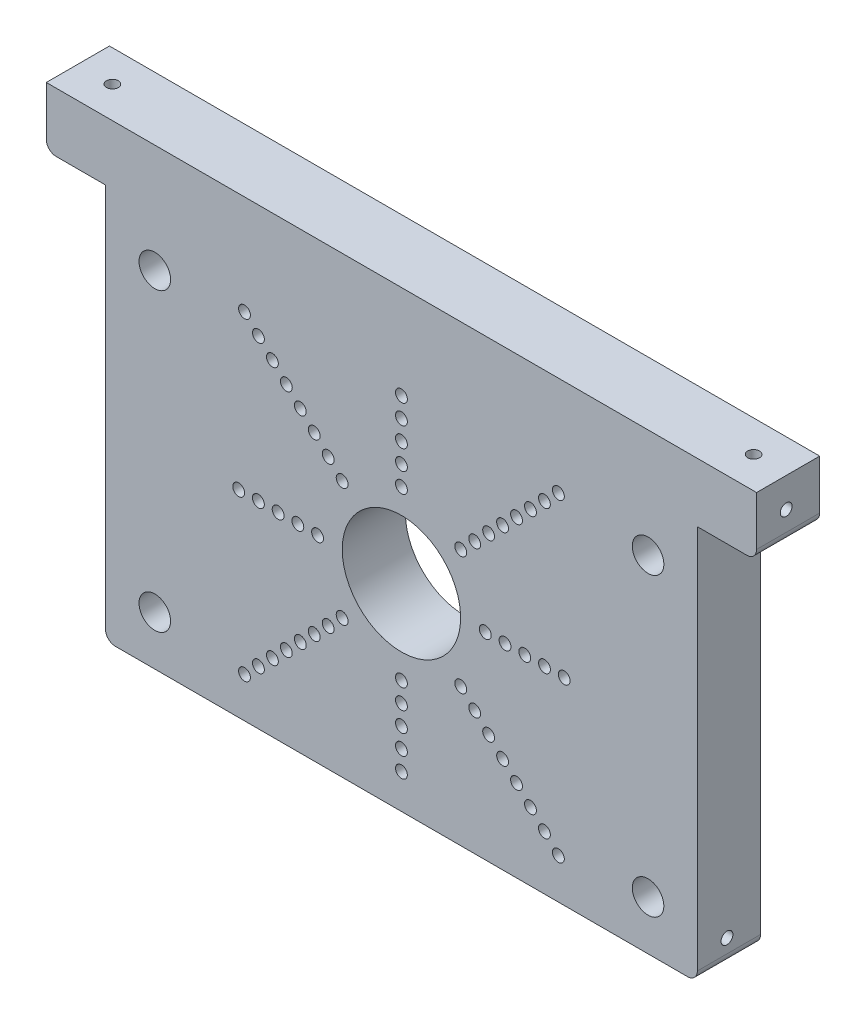
SolidWorks part; units mm, degrees
ref_plane "Front Plane" through (0, 0, 0) normal (0, 0, 1) x (1, 0, 0)
ref_plane "Top Plane" through (0, 0, 0) normal (0, 1, 0) x (1, 0, 0)
ref_plane "Right Plane" through (0, 0, 0) normal (1, 0, 0) x (0, 0, -1)
sketch "Sketch1" plane through (0, 0, 0) normal (0, 0, 1) x (1, 0, 0)
  line L1 (150, 100) -> (-150, 100)
  line L2 (150, 100) -> (150, -100)
  line L3 (150, -100) -> (-150, -100)
  line L4 (-150, 100) -> (-150, -100)
  circle A0 centre (125, 75) radius 8
  circle A1 centre (125, -75) radius 8
  circle A2 centre (-125, -75) radius 8
  circle A3 centre (-125, 75) radius 8
  point P0 (0, 0)
  dimension "D7" = 16
  dimension "D8" = 16
  dimension "D9" = 16
  dimension "D10" = 16
  dimension "D1" = 200
  dimension "D2" = 300
extrude "Boss-Extrude1" add sketch "Sketch1" along normal blind 32
sketch "Sketch2" plane through (0, 0, 32) normal (0, 0, 1) x (1, 0, 0)
  line L7 (-150, -100) -> (-150, 100) construction
  circle A2 centre (58.3363, -58.3363) radius 3
  circle A3 centre (51.2652, -51.2652) radius 3
  circle A4 centre (44.1942, -44.1942) radius 3
  circle A5 centre (37.1231, -37.1231) radius 3
  circle A6 centre (30.052, -30.052) radius 3
  circle A8 centre (65.4074, -65.4074) radius 3
  circle A9 centre (72.4784, -72.4784) radius 3
  circle A10 centre (42.5, 0) radius 3
  circle A11 centre (52.5, 0) radius 3
  circle A12 centre (62.5, 0) radius 3
  circle A13 centre (72.5, 0) radius 3
  circle A14 centre (82.5, 0) radius 3
  circle A15 centre (79.5495, -79.5495) radius 3
  circle A18 centre (0, -82.5) radius 3
  circle A19 centre (0, -72.5) radius 3
  circle A20 centre (0, -62.5) radius 3
  circle A21 centre (0, -52.5) radius 3
  circle A22 centre (0, -42.5) radius 3
  circle A24 centre (-65.4074, -65.4074) radius 3
  circle A25 centre (-72.4784, -72.4784) radius 3
  circle A26 centre (-58.3363, -58.3363) radius 3
  circle A27 centre (-51.2652, -51.2652) radius 3
  circle A28 centre (-44.1942, -44.1942) radius 3
  circle A29 centre (-37.1231, -37.1231) radius 3
  circle A30 centre (-30.052, -30.052) radius 3
  circle A31 centre (-79.5495, -79.5495) radius 3
  circle A34 centre (-82.5, 0) radius 3
  circle A35 centre (-72.5, 0) radius 3
  circle A36 centre (-62.5, 0) radius 3
  circle A37 centre (-52.5, 0) radius 3
  circle A38 centre (-42.5, 0) radius 3
  circle A40 centre (-65.4074, 65.4074) radius 3
  circle A41 centre (-72.4784, 72.4784) radius 3
  circle A42 centre (-58.3363, 58.3363) radius 3
  circle A43 centre (-51.2652, 51.2652) radius 3
  circle A44 centre (-44.1942, 44.1942) radius 3
  circle A45 centre (-37.1231, 37.1231) radius 3
  circle A46 centre (-30.052, 30.052) radius 3
  circle A47 centre (-79.5495, 79.5495) radius 3
  circle A50 centre (0, 82.5) radius 3
  circle A51 centre (0, 72.5) radius 3
  circle A52 centre (0, 62.5) radius 3
  circle A53 centre (0, 52.5) radius 3
  circle A54 centre (0, 42.5) radius 3
  circle A56 centre (65.4074, 65.4074) radius 3
  circle A57 centre (72.4784, 72.4784) radius 3
  circle A58 centre (58.3363, 58.3363) radius 3
  circle A59 centre (51.2652, 51.2652) radius 3
  circle A60 centre (44.1942, 44.1942) radius 3
  circle A61 centre (37.1231, 37.1231) radius 3
  circle A62 centre (30.052, 30.052) radius 3
  circle A63 centre (79.5495, 79.5495) radius 3
  point P128 (0, 0)
  point P138 (0, 0)
  dimension "D2" = 8
extrude "Cut-Extrude2" cut sketch "Sketch2" against normal blind 32
sketch "Sketch4" plane through (0, 0, 0) normal (0, 0, -1) x (-1, 0, 0)
  line L0 (0, 100) -> (0, 80) construction
  line L1 (-150, 100) -> (150, 100) construction
  line L2 (150, 0) -> (150, 7.5) construction
  line L3 (-7.5, -18.1066) -> (-7.5, -83.9696)
  line L4 (150, 7.5) -> (150, -7.5) construction
  line L7 (0, 100) -> (0, 80) construction
  line L8 (0, -100) -> (0, -80) construction
  line L9 (150, 100) -> (150, -100) construction
  line L11 (150, -100) -> (-150, -100) construction
  line L12 (139.6966, 7.5) -> (18.1066, 7.5)
  line L14 (-139.6966, -7.5) -> (-18.1066, -7.5)
  line L15 (150, -7.5) -> (150, 7.5)
  line L16 (-91.9422, 81.3356) -> (-18.1066, 7.5)
  line L17 (-7.5, 83.9696) -> (-7.5, 18.1066)
  line L18 (77.2382, 87.8448) -> (7.5, 18.1066)
  line L19 (139.6966, 7.5) -> (18.1066, 7.5)
  line L20 (91.9422, -81.3356) -> (18.1066, -7.5)
  line L21 (7.5, -83.9696) -> (7.5, -18.1066)
  line L22 (-77.2382, -87.8448) -> (-7.5, -18.1066)
  line L23 (-18.1066, -7.5) -> (-91.9422, -81.3356)
  line L25 (-18.1066, 7.5) -> (-139.6966, 7.5)
  line L26 (-18.1066, 7.5) -> (-139.6966, 7.5)
  line L28 (-7.5, 18.1066) -> (-77.2382, 87.8448)
  line L30 (7.5, 18.1066) -> (7.5, 83.9696)
  line L33 (18.1066, 7.5) -> (91.9422, 81.3356)
  line L35 (18.1066, -7.5) -> (139.6966, -7.5)
  line L37 (7.5, -18.1066) -> (77.2382, -87.8448)
  arc A0 (0, 80) -> (0, -80) centre (47.1429, 0) cw
  arc A1 (0, 80) -> (0, -80) centre (-47.1429, 0) ccw
  point P40 (0, 0)
  dimension "D5" = 15
  dimension "D1" = 20
  dimension "D4" = 20
  dimension "D6" = 8
extrude "Cut-Extrude4" cut sketch "Sketch4" against normal blind 16 contours L16 A1 L25 | L17 A1 L28 | A0 L30 L18 | A0 L33 L12 | A0 L35 L20 | A0 L37 L21 | L22 A1 L3 | L14 A1 L23
fillet "Fillet4" radius 10 8 edges at (-18.1066, 7.5, 8) (-7.5, 18.1066, 8) (7.5, 18.1066, 8) (18.1066, 7.5, 8) (18.1066, -7.5, 8) (7.5, -18.1066, 8) (-7.5, -18.1066, 8) (-18.1066, -7.5, 8)
fillet "Fillet8" radius 10 16 edges at (-91.9422, -81.3356, 8) (-139.6966, -7.5, 8) (-139.6966, 7.5, 8) (-91.9422, 81.3356, 8) (-77.2382, 87.8448, 8) (7.5, 83.9696, 8) (-7.5, 83.9696, 8) (77.2382, 87.8448, 8) (91.9422, 81.3356, 8) (139.6966, -7.5, 8) (139.6966, 7.5, 8) (91.9422, -81.3356, 8) (77.2382, -87.8448, 8) (7.5, -83.9696, 8) (-7.5, -83.9696, 8) (-77.2382, -87.8448, 8)
sketch "Sketch5" plane through (0, 0, 0) normal (0, 0, -1) x (-1, 0, 0)
  line L0 (-150, 100) -> (-180, 100)
  line L1 (-180, 100) -> (-180, 130)
  line L2 (-180, 130) -> (180, 130)
  line L3 (180, 130) -> (180, 100)
  line L4 (180, 100) -> (150, 100)
  line L5 (-150, 100) -> (150, 100) construction
  line L6 (-150, 100) -> (150, 100)
  dimension "D1" = 30
  dimension "D2" = 30
extrude "Boss-Extrude2" add sketch "Sketch5" against normal blind 32
sketch "Sketch6" plane through (0, 0, 0) normal (0, 0, -1) x (-1, 0, 0)
  line L0 (150, -100) -> (-150, 100) construction
  circle A0 centre (0, 0) radius 30
  dimension "D1" = 60
extrude "Cut-Extrude5" cut sketch "Sketch6" against normal blind 32
fillet "Fillet9" radius 5 4 edges at (-180, 100, 16) (-150, -100, 16) (180, 100, 16) (150, -100, 16)
sketch "Sketch7" plane through (-180, 0, 0) normal (-1, 0, 0) x (0, 0, 1)
  line L1 (32, 130) -> (17, 130)
  line L2 (32, 130) -> (32, 115)
  line L3 (32, 115) -> (17, 115)
  line L4 (17, 130) -> (17, 115)
  circle A0 centre (17, 115) radius 3
  dimension "D3" = 6
  dimension "D1" = 15
  dimension "D2" = 15
extrude "Cut-Extrude6" cut sketch "Sketch7" against normal blind 10 contours L4 A0 L3 | L3 A0 L4
sketch "Sketch8" plane through (180, 0, 0) normal (1, 0, 0) x (0, 0, -1)
  line L1 (-32, 130) -> (-17, 130)
  line L2 (-32, 130) -> (-32, 115)
  line L3 (-32, 115) -> (-17, 115)
  line L4 (-17, 130) -> (-17, 115)
  circle A0 centre (-17, 115) radius 3
  dimension "D3" = 6
  dimension "D1" = 15
  dimension "D2" = 15
extrude "Cut-Extrude7" cut sketch "Sketch8" against normal blind 10 contours L3 A0 L4 | L4 A0 L3
sketch "Sketch9" plane through (150, 0, 0) normal (1, 0, 0) x (0, 0, -1)
  line L1 (-32, -100) -> (-17, -100)
  line L2 (-32, -100) -> (-32, -88)
  circle A0 centre (-17, -88) radius 3
  dimension "D3" = 6
  dimension "D1" = 12
  dimension "D2" = 15
extrude "Cut-Extrude8" cut sketch "Sketch9" against normal blind 10 contours A0
sketch "Sketch10" plane through (-150, 0, 0) normal (-1, 0, 0) x (0, 0, 1)
  line L1 (32, -100) -> (17, -100)
  line L2 (32, -100) -> (32, -88)
  circle A0 centre (17, -88) radius 3
  dimension "D3" = 6
  dimension "D1" = 15
  dimension "D2" = 12
extrude "Cut-Extrude9" cut sketch "Sketch10" against normal blind 10 contours A0
sketch "Sketch11" plane through (0, 100, 0) normal (0, -1, 0) x (-1, 0, 0)
  line L0 (160.6531, -18.3641) -> (164.3469, -13.6359) construction
  line L3 (150, 0) -> (175, 0)
  circle A0 centre (162.5, -16) radius 3
  circle A1 centre (-162.5, -16) radius 3
  dimension "D1" = 6
  dimension "D2" = 6
extrude "Cut-Extrude11" cut sketch "Sketch11" against normal blind 153 contours L0 A0 | A0 L0 | A1
sketch "Sketch12" plane through (0, -100, 0) normal (0, -1, 0) x (-1, 0, 0)
  line L1 (150, -32) -> (138, -32)
  circle A0 centre (138, -17) radius 3
  circle A1 centre (-138, -17) radius 3
  dimension "D3" = 6
  dimension "D6" = 6
  dimension "D1" = 12
extrude "Cut-Extrude12" cut sketch "Sketch12" against normal blind 5 contours A0 | A1
